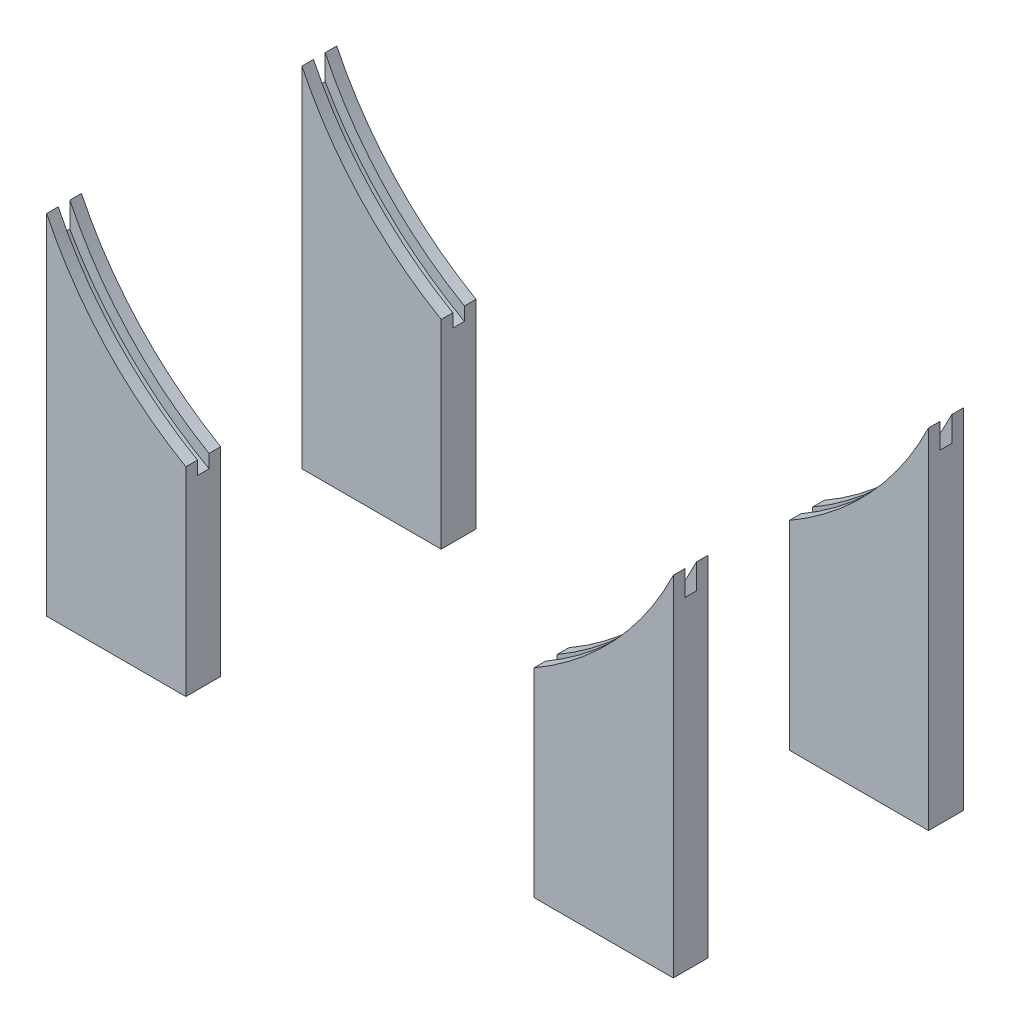
SolidWorks part; units mm, degrees
ref_plane "Front Plane" through (0, 0, 0) normal (0, 0, 1) x (1, 0, 0)
ref_plane "Top Plane" through (0, 0, 0) normal (0, 1, 0) x (1, 0, 0)
ref_plane "Right Plane" through (0, 0, 0) normal (1, 0, 0) x (0, 0, -1)
sketch "Sketch1" plane through (0, 0, 0) normal (0, 0, 1) x (1, 0, 0)
  circle A0 centre (0, 0) radius 150
  circle A1 centre (0, 0) radius 155
  dimension "D1" = 300
  dimension "D2" = 5
ref_plane "Plane1" through (0, 0, 2.5) normal (0, 0, 1) x (1, 0, 0)
sketch "Sketch6" plane through (0, 0, 2.5) normal (0, 0, 1) x (1, 0, 0)
  circle A1 centre (0, 0) radius 155
  dimension "D1" = 310
sketch "Sketch7" plane through (0, 0, 2.5) normal (0, 0, 1) x (1, 0, 0)
  line L0 (75, -135.6466) -> (75, -215.6466)
  line L1 (75, -215.6466) -> (135, -215.6466)
  line L2 (135, -215.6466) -> (135, -76.1577)
  circle A0 centre (0, 0) radius 155 construction
  arc A1 (75, -135.6466) -> (135, -76.1577) centre (0, 0) ccw
  dimension "D1" = 80
  dimension "D2" = 60
  dimension "D3" = 75
extrude "Boss-Extrude4" add sketch "Sketch7" along normal mid plane 5 separate body
sketch "Sketch8" plane through (0, 0, 5) normal (0, 0, 1) x (1, 0, 0)
  line L0 (75, -215.6466) -> (135, -215.6466)
  line L1 (135, -215.6466) -> (135, -65.3835)
  line L2 (75, -129.9038) -> (75, -215.6466)
  circle A1 centre (0, 0) radius 150 construction
  arc A3 (135, -65.3835) -> (75, -129.9038) centre (0, 0) cw
extrude "Boss-Extrude5" add sketch "Sketch8" along normal blind 5
mirror "Mirror1" about plane through (0, 0, 2.5) normal (0, 0, 1) of "Boss-Extrude5"
mirror "Mirror2" about plane through (0, 0, 0) normal (1, 0, 0) of bodies 111
ref_plane "Plane2" through (0, 0, 57.5) normal (0, 0, 1) x (1, 0, 0)
mirror "Mirror3" about plane through (0, 0, 57.5) normal (0, 0, 1) of bodies 111 112
